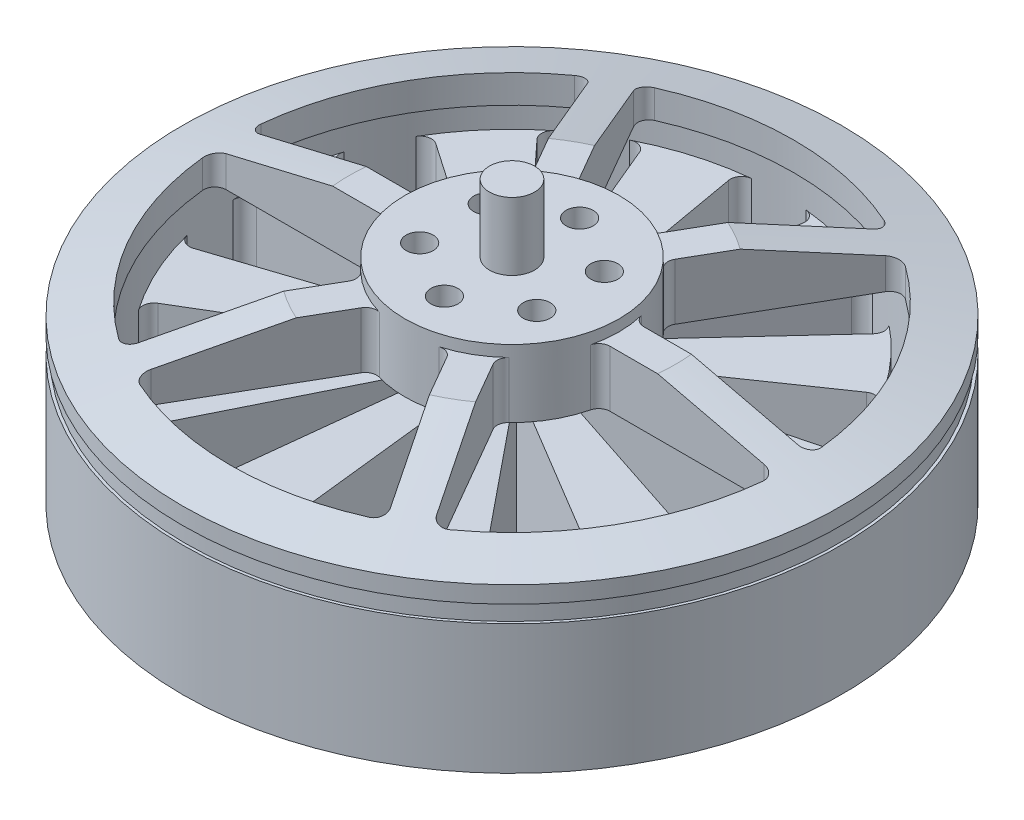
SolidWorks part; units mm, degrees
material "AISI 304"
ref_plane "前视基准面" through (0, 0, 0) normal (0, 0, 1) x (1, 0, 0)
ref_plane "上视基准面" through (0, 0, 0) normal (0, 1, 0) x (1, 0, 0)
ref_plane "右视基准面" through (0, 0, 0) normal (1, 0, 0) x (0, 0, -1)
sketch "Sketch1" plane through (0, 0, 0) normal (0, 1, 0) x (1, 0, 0)
  line L0 (0, 17.0731) -> (0, -17.4664) construction
  line L1 (-18.3889, 0) -> (24.4664, 0) construction
  line L2 (14.5, -3) -> (12.1347, -3)
  line L3 (2, 15.5) -> (-2, 15.5)
  line L4 (-3, 14.5) -> (-3, 12.1347)
  line L5 (3, 14.5) -> (3, 12.1347)
  line L6 (14.5, 3) -> (12.1347, 3)
  line L7 (15.5, -2) -> (15.5, 2)
  line L8 (-3, -14.5) -> (-3, -12.1347)
  line L9 (3, -14.5) -> (3, -12.1347)
  line L10 (-2, -15.5) -> (2, -15.5)
  line L11 (-14.5, 3) -> (-12.1347, 3)
  line L12 (-14.5, -3) -> (-12.1347, -3)
  line L13 (-15.5, 2) -> (-15.5, -2)
  arc A0 (-3, 12.1347) -> (-12.1347, 3) centre (0, 0) ccw
  circle A1 centre (0, 0) radius 6
  circle A2 centre (0, 12.5) radius 1.2
  arc A3 (3, 14.5) -> (2, 15.5) centre (2, 14.5) ccw
  arc A4 (-2, 15.5) -> (-3, 14.5) centre (-2, 14.5) ccw
  circle A5 centre (12.5, 0) radius 1.2
  arc A6 (15.5, 2) -> (14.5, 3) centre (14.5, 2) ccw
  arc A7 (14.5, -3) -> (15.5, -2) centre (14.5, -2) ccw
  circle A8 centre (0, -12.5) radius 1.2
  arc A9 (2, -15.5) -> (3, -14.5) centre (2, -14.5) ccw
  arc A10 (-3, -14.5) -> (-2, -15.5) centre (-2, -14.5) ccw
  circle A11 centre (-12.5, 0) radius 1.2
  arc A12 (-15.5, -2) -> (-14.5, -3) centre (-14.5, -2) ccw
  arc A13 (-14.5, 3) -> (-15.5, 2) centre (-14.5, 2) ccw
  arc A14 (-12.1347, -3) -> (-3, -12.1347) centre (0, 0) ccw
  arc A15 (12.1347, 3) -> (3, 12.1347) centre (0, 0) ccw
  arc A16 (3, -12.1347) -> (12.1347, -3) centre (0, 0) ccw
  circle A17 centre (0, 0) radius 8.5 construction
  arc A18 (-3, 7.953) -> (-7.953, 3) centre (0, 0) ccw construction
  arc A19 (-3.5647, 9.45) -> (-9.45, 3.5647) centre (0, 0) ccw
  arc A20 (-2.4353, 6.456) -> (-6.456, 2.4353) centre (0, 0) ccw
  arc A21 (-2.4353, 6.456) -> (-3.5647, 9.45) centre (-3, 7.953) ccw
  arc A22 (-9.45, 3.5647) -> (-6.456, 2.4353) centre (-7.953, 3) ccw
  arc A23 (7.953, 3) -> (3, 7.953) centre (0, 0) ccw construction
  arc A24 (9.45, 3.5647) -> (3.5647, 9.45) centre (0, 0) ccw
  arc A25 (6.456, 2.4353) -> (2.4353, 6.456) centre (0, 0) ccw
  arc A26 (6.456, 2.4353) -> (9.45, 3.5647) centre (7.953, 3) ccw
  arc A27 (3.5647, 9.45) -> (2.4353, 6.456) centre (3, 7.953) ccw
  arc A28 (3, -7.953) -> (7.953, -3) centre (0, 0) ccw construction
  arc A29 (3.5647, -9.45) -> (9.45, -3.5647) centre (0, 0) ccw
  arc A30 (2.4353, -6.456) -> (6.456, -2.4353) centre (0, 0) ccw
  arc A31 (2.4353, -6.456) -> (3.5647, -9.45) centre (3, -7.953) ccw
  arc A32 (9.45, -3.5647) -> (6.456, -2.4353) centre (7.953, -3) ccw
  arc A33 (-7.953, -3) -> (-3, -7.953) centre (0, 0) ccw construction
  arc A34 (-9.45, -3.5647) -> (-3.5647, -9.45) centre (0, 0) ccw
  arc A35 (-6.456, -2.4353) -> (-2.4353, -6.456) centre (0, 0) ccw
  arc A36 (-6.456, -2.4353) -> (-9.45, -3.5647) centre (-7.953, -3) ccw
  arc A37 (-3.5647, -9.45) -> (-2.4353, -6.456) centre (-3, -7.953) ccw
  point P16 (3, 15.5)
  point P19 (-3, 15.5)
  point P52 (0, 0)
  point P53 (-6.0104, 6.0104)
  point P63 (6.0104, 6.0104)
  point P70 (6.0104, -6.0104)
  point P77 (-6.0104, -6.0104)
  point P82 (0, 0)
  dimension "D1" = 25
  dimension "D2" = 12
  dimension "D5" = 2.4
  dimension "D6" = 1
  dimension "D9" = 17
  dimension "D12" = 1.6
  dimension "D3" = 15.5
  dimension "D4" = 6
  dimension "D7" = 12.5
  dimension "D10" = 3
  dimension "D11" = 3
  dimension "D8" = 4
  dimension "D13" = 4
extrude "Boss-Extrude1" add sketch "Sketch1" along normal blind 4.4
cosmetic thread "Cosmetic Thread1" parameters "D2"=3
cosmetic thread "Cosmetic Thread2" parameters "D2"=3
cosmetic thread "Cosmetic Thread3" parameters "D2"=3
cosmetic thread "Cosmetic Thread4" parameters "D2"=3
sketch "Sketch2" plane through (0, 4.4, 0) normal (0, 1, 0) x (1, 0, 0)
  arc A0 (-12.1347, -3) -> (-3, -12.1347) centre (0, 0) ccw
  arc A1 (-12.1347, -3) -> (-10.7247, -2.4457) centre (-12.5, 0) ccw
  arc A2 (-3, 12.1347) -> (-2.4457, 10.7247) centre (0, 12.5) ccw
  arc A3 (12.1347, 3) -> (10.7247, 2.4457) centre (12.5, 0) ccw
  arc A4 (3, -12.1347) -> (2.4457, -10.7247) centre (0, -12.5) ccw
  arc A5 (-3, 12.1347) -> (-12.1347, 3) centre (0, 0) ccw
  arc A6 (12.1347, 3) -> (3, 12.1347) centre (0, 0) ccw
  arc A7 (3, -12.1347) -> (12.1347, -3) centre (0, 0) ccw
  arc A8 (-10.7247, -2.4457) -> (-2.4457, -10.7247) centre (0, 0) ccw
  arc A9 (-2.4457, 10.7247) -> (-10.7247, 2.4457) centre (0, 0) ccw
  arc A10 (10.7247, 2.4457) -> (2.4457, 10.7247) centre (0, 0) ccw
  arc A11 (2.4457, -10.7247) -> (10.7247, -2.4457) centre (0, 0) ccw
  arc A12 (2.4457, 10.7247) -> (3, 12.1347) centre (0, 12.5) ccw
  arc A13 (10.7247, -2.4457) -> (12.1347, -3) centre (12.5, 0) ccw
  arc A14 (-2.4457, -10.7247) -> (-3, -12.1347) centre (0, -12.5) ccw
  arc A15 (-10.7247, 2.4457) -> (-12.1347, 3) centre (-12.5, 0) ccw
  point P18 (0, 0)
  point P24 (0, 0)
  point P25 (0, 0)
  point P26 (0, 0)
  dimension "D2" = 22
  dimension "D3" = 25
  dimension "D1" = 4
extrude "Boss-Extrude2" add sketch "Sketch2" along normal blind 4.4
sketch "Sketch3" plane through (0, 8.8, 0) normal (0, 1, 0) x (1, 0, 0)
  line L0 (-18.6186, 0) -> (21.8055, 0) construction
  line L1 (0, 15.9767) -> (0, -16.424) construction
  line L2 (-12.4789, 12.4789) -> (0, 0) construction
  line L3 (-8.4531, 7.0389) -> (-2.7071, 1.2929)
  line L4 (-7.0389, 8.4531) -> (-1.2929, 2.7071)
  line L5 (8.4531, 7.0389) -> (2.7071, 1.2929)
  line L6 (-13.186, 11.7718) -> (-0.7071, -0.7071) construction
  line L7 (-11.7718, 13.186) -> (0.7071, 0.7071) construction
  line L8 (7.0389, 8.4531) -> (1.2929, 2.7071)
  line L9 (7.0389, -8.4531) -> (1.2929, -2.7071)
  line L10 (8.4531, -7.0389) -> (2.7071, -1.2929)
  line L11 (-8.4531, -7.0389) -> (-2.7071, -1.2929)
  line L12 (-7.0389, -8.4531) -> (-1.2929, -2.7071)
  arc A0 (-2.7071, 1.2929) -> (-2.7071, -1.2929) centre (0, 0) ccw
  arc A1 (-7.0389, 8.4531) -> (-8.4531, 7.0389) centre (0, 0) ccw
  arc A2 (8.4531, 7.0389) -> (7.0389, 8.4531) centre (0, 0) ccw
  arc A3 (7.0389, -8.4531) -> (8.4531, -7.0389) centre (0, 0) ccw
  arc A4 (-8.4531, -7.0389) -> (-7.0389, -8.4531) centre (0, 0) ccw
  arc A5 (1.2929, 2.7071) -> (-1.2929, 2.7071) centre (0, 0) ccw
  arc A6 (2.7071, -1.2929) -> (2.7071, 1.2929) centre (0, 0) ccw
  arc A7 (-1.2929, -2.7071) -> (1.2929, -2.7071) centre (0, 0) ccw
  point P30 (0, 0)
  dimension "D1" = 6
  dimension "D5" = 22
  dimension "D2" = 45
  dimension "D3" = 1
  dimension "D4" = 1
  dimension "D6" = 4
extrude "Boss-Extrude3" add sketch "Sketch3" against normal blind 4.4
sketch "Sketch4" plane through (0, 4.4, 0) normal (0, -1, 0) x (1, 0, 0)
  circle A0 centre (0, 0) radius 3
extrude "Boss-Extrude4" add sketch "Sketch4" along normal blind 6
sketch "Sketch5" plane through (0, 8.8, 0) normal (0, 1, 0) x (1, 0, 0)
  circle A0 centre (0, 0) radius 2
  dimension "D1" = 4
extrude "Boss-Extrude5" add sketch "Sketch5" along normal blind 25
sketch "Sketch6" plane through (0, 0, 0) normal (0, 0, 1) x (1, 0, 0)
  line L0 (0, 28.4377) -> (0, -3.1922) construction
  line L1 (-25.25, 8.8) -> (-29.25, 8.8)
  line L3 (-29.25, 8.8) -> (-29.25, 23.3)
  line L4 (-29.25, 23.3) -> (-14.5, 26.8)
  line L5 (-14.5, 26.8) -> (-9.5, 26.8)
  line L6 (-9.5, 26.8) -> (-9.5, 27.8)
  line L7 (-9.5, 27.8) -> (0, 27.8)
  line L8 (-12.1347, 0) -> (-3, 0) construction
  line L10 (0, 27.8) -> (0, 21.8)
  line L11 (0, 21.8) -> (-25.25, 21.8)
  line L12 (-25.25, 21.8) -> (-25.25, 8.8)
  dimension "D1" = 27.8
  dimension "D2" = 9.5
  dimension "D3" = 5
  dimension "D4" = 29.25
  dimension "D5" = 1
  dimension "D6" = 14.5
  dimension "D7" = 4
  dimension "D8" = 6
revolve "Revolve2" add sketch "Sketch6" angle 360 about L0
sketch "Sketch7" plane through (0, 26.8, 0) normal (0, 1, 0) x (1, 0, 0)
  line L0 (-38.4586, 0) -> (33.9217, 0) construction
  line L1 (0, 30.0441) -> (0, -31.152) construction
  line L2 (-10.6357, 21.4215) -> (-3.8, 9.5818)
  line L3 (0, 0) -> (-16.9032, 29.2772) construction
  line L4 (0, 0) -> (16.9032, 29.2772) construction
  line L5 (10.6357, 21.4215) -> (3.8, 9.5818)
  line L6 (13.2338, 19.9215) -> (6.3981, 8.0818)
  line L7 (23.8694, 1.5) -> (10.198, 1.5)
  line L8 (23.8694, -1.5) -> (10.198, -1.5)
  line L9 (13.2338, -19.9215) -> (6.3981, -8.0818)
  line L10 (10.6357, -21.4215) -> (3.8, -9.5818)
  line L11 (-10.6357, -21.4215) -> (-3.8, -9.5818)
  line L12 (-13.2338, -19.9215) -> (-6.3981, -8.0818)
  line L13 (-23.8694, -1.5) -> (-10.198, -1.5)
  line L14 (-23.8694, 1.5) -> (-10.198, 1.5)
  line L15 (-13.2338, 19.9215) -> (-6.3981, 8.0818)
  arc A2 (10.1767, 22.8349) -> (-10.1767, 22.8349) centre (0, 0) ccw
  arc A3 (2.6545, 9.1216) -> (-2.6545, 9.1216) centre (0, 0) ccw
  arc A4 (-3.8, 9.5818) -> (-2.6545, 9.1216) centre (-2.934, 10.0818) ccw
  arc A5 (3.8, 9.5818) -> (2.6545, 9.1216) centre (2.934, 10.0818) cw
  arc A6 (10.6357, 21.4215) -> (10.1767, 22.8349) centre (9.7697, 21.9215) ccw
  arc A7 (-10.6357, 21.4215) -> (-10.1767, 22.8349) centre (-9.7697, 21.9215) cw
  arc A8 (13.2338, 19.9215) -> (14.6873, 20.2308) centre (14.0998, 19.4215) cw
  arc A9 (6.3981, 8.0818) -> (6.5723, 6.8597) centre (7.2641, 7.5818) ccw
  arc A10 (9.2268, 2.2619) -> (6.5723, 6.8597) centre (0, 0) ccw
  arc A11 (10.198, 1.5) -> (9.2268, 2.2619) centre (10.198, 2.5) cw
  arc A12 (23.8694, 1.5) -> (24.864, 2.6042) centre (23.8694, 2.5) ccw
  arc A13 (24.864, 2.6042) -> (14.6873, 20.2308) centre (0, 0) ccw
  arc A14 (23.8694, -1.5) -> (24.864, -2.6042) centre (23.8694, -2.5) cw
  arc A15 (10.198, -1.5) -> (9.2268, -2.2619) centre (10.198, -2.5) ccw
  arc A16 (6.5723, -6.8597) -> (9.2268, -2.2619) centre (0, 0) ccw
  arc A17 (6.3981, -8.0818) -> (6.5723, -6.8597) centre (7.2641, -7.5818) cw
  arc A18 (13.2338, -19.9215) -> (14.6873, -20.2308) centre (14.0998, -19.4215) ccw
  arc A19 (14.6873, -20.2308) -> (24.864, -2.6042) centre (0, 0) ccw
  arc A20 (10.6357, -21.4215) -> (10.1767, -22.8349) centre (9.7697, -21.9215) cw
  arc A21 (3.8, -9.5818) -> (2.6545, -9.1216) centre (2.934, -10.0818) ccw
  arc A22 (-2.6545, -9.1216) -> (2.6545, -9.1216) centre (0, 0) ccw
  arc A23 (-3.8, -9.5818) -> (-2.6545, -9.1216) centre (-2.934, -10.0818) cw
  arc A24 (-10.6357, -21.4215) -> (-10.1767, -22.8349) centre (-9.7697, -21.9215) ccw
  arc A25 (-10.1767, -22.8349) -> (10.1767, -22.8349) centre (0, 0) ccw
  arc A26 (-13.2338, -19.9215) -> (-14.6873, -20.2308) centre (-14.0998, -19.4215) cw
  arc A27 (-6.3981, -8.0818) -> (-6.5723, -6.8597) centre (-7.2641, -7.5818) ccw
  arc A28 (-9.2268, -2.2619) -> (-6.5723, -6.8597) centre (0, 0) ccw
  arc A29 (-10.198, -1.5) -> (-9.2268, -2.2619) centre (-10.198, -2.5) cw
  arc A30 (-23.8694, -1.5) -> (-24.864, -2.6042) centre (-23.8694, -2.5) ccw
  arc A31 (-24.864, -2.6042) -> (-14.6873, -20.2308) centre (0, 0) ccw
  arc A32 (-23.8694, 1.5) -> (-24.864, 2.6042) centre (-23.8694, 2.5) cw
  arc A33 (-10.198, 1.5) -> (-9.2268, 2.2619) centre (-10.198, 2.5) ccw
  arc A34 (-6.5723, 6.8597) -> (-9.2268, 2.2619) centre (0, 0) ccw
  arc A35 (-6.3981, 8.0818) -> (-6.5723, 6.8597) centre (-7.2641, 7.5818) cw
  arc A36 (-13.2338, 19.9215) -> (-14.6873, 20.2308) centre (-14.0998, 19.4215) ccw
  arc A37 (-14.6873, 20.2308) -> (-24.864, 2.6042) centre (0, 0) ccw
  point P12 (-3.3914, 8.874)
  point P17 (3.3914, 8.874)
  point P85 (0, 0)
  dimension "D1" = 25
  dimension "D2" = 9.5
  dimension "D7" = 1
  dimension "D3" = 1.5
  dimension "D4" = 30
  dimension "D5" = 30
  dimension "D6" = 6.7828
  dimension "D8" = 6
extrude "Cut-Extrude1" cut sketch "Sketch7" against normal blind 19
sketch "Sketch8" plane through (0, 0, 0) normal (0, 0, 1) x (1, 0, 0)
  line L0 (0, 34.8317) -> (0, -3.8139) construction
  line L1 (0, 20.8) -> (-23.8, 20.8)
  line L2 (-23.8, 20.8) -> (-23.8, 8.8)
  line L3 (-25.25, 8.8) -> (25.25, 8.8) construction
  line L4 (-23.8, 8.8) -> (0, 8.8)
  line L5 (0, 20.8) -> (0, 8.8)
  dimension "D1" = 12
  dimension "D2" = 23.8
revolve "Revolve3" add sketch "Sketch8" angle 360 about L0
sketch "Sketch9" plane through (0, 20.8, 0) normal (0, 1, 0) x (1, 0, 0)
  line L0 (0, 24.4521) -> (0, 3.8491) construction
  line L1 (-3.2903, 22.5095) -> (0, 3.8491)
  line L2 (3.2903, 22.5095) -> (0, 3.8491)
  line L3 (9.4015, 20.7151) -> (2.081, 3.2381)
  line L4 (14.9375, 17.1573) -> (2.081, 3.2381)
  line L5 (19.1085, 12.3438) -> (3.5013, 1.599)
  line L6 (21.8422, 6.3578) -> (3.5013, 1.599)
  line L7 (22.7486, 0.0534) -> (3.8099, -0.5478)
  line L8 (21.8121, -6.4603) -> (3.8099, -0.5478)
  line L9 (19.1662, -12.2539) -> (2.9089, -2.5206)
  line L10 (14.8568, -17.2272) -> (2.9089, -2.5206)
  line L11 (9.4987, -20.6707) -> (1.0844, -3.6932)
  line L12 (3.1846, -22.5247) -> (1.0844, -3.6932)
  line L13 (-3.1846, -22.5247) -> (-1.0844, -3.6932)
  line L14 (-9.4987, -20.6707) -> (-1.0844, -3.6932)
  line L15 (-14.8568, -17.2272) -> (-2.9089, -2.5206)
  line L16 (-19.1662, -12.2539) -> (-2.9089, -2.5206)
  line L17 (-21.8121, -6.4603) -> (-3.8099, -0.5478)
  line L18 (-22.7486, 0.0534) -> (-3.8099, -0.5478)
  line L19 (-21.8422, 6.3578) -> (-3.5013, 1.599)
  line L20 (-19.1085, 12.3438) -> (-3.5013, 1.599)
  line L21 (-14.9375, 17.1573) -> (-2.081, 3.2381)
  line L22 (-9.4015, 20.7151) -> (-2.081, 3.2381)
  circle A0 centre (0, 0) radius 23.8 construction
  arc A1 (2.4066, 23.678) -> (-2.4066, 23.678) centre (0, 0) ccw
  arc A2 (3.2903, 22.5095) -> (2.4066, 23.678) centre (2.3055, 22.6831) ccw
  arc A3 (-3.2903, 22.5095) -> (-2.4066, 23.678) centre (-2.3055, 22.6831) cw
  arc A4 (14.8259, 18.6181) -> (10.7767, 21.2203) centre (0, 0) ccw
  arc A5 (9.4015, 20.7151) -> (10.7767, 21.2203) centre (10.3239, 20.3287) cw
  arc A6 (14.9375, 17.1573) -> (14.8259, 18.6181) centre (14.203, 17.8358) ccw
  arc A7 (22.538, 7.647) -> (20.5385, 12.0254) centre (0, 0) ccw
  arc A8 (19.1085, 12.3438) -> (20.5385, 12.0254) centre (19.6756, 11.5201) cw
  arc A9 (21.8422, 6.3578) -> (22.538, 7.647) centre (21.5911, 7.3257) ccw
  arc A10 (23.0945, -5.7519) -> (23.7795, -0.9876) centre (0, 0) ccw
  arc A11 (22.7486, 0.0534) -> (23.7795, -0.9876) centre (22.7804, -0.9461) cw
  arc A12 (21.8121, -6.4603) -> (23.0945, -5.7519) centre (22.1241, -5.5102) ccw
  arc A13 (16.3186, -17.3246) -> (19.4707, -13.687) centre (0, 0) ccw
  arc A14 (19.1662, -12.2539) -> (19.4707, -13.687) centre (18.6526, -13.1119) cw
  arc A15 (14.8568, -17.2272) -> (16.3186, -17.3246) centre (15.633, -16.5967) ccw
  arc A16 (4.3617, -23.3969) -> (8.98, -22.0409) centre (0, 0) ccw
  arc A17 (9.4987, -20.6707) -> (8.98, -22.0409) centre (8.6027, -21.1148) cw
  arc A18 (3.1846, -22.5247) -> (4.3617, -23.3969) centre (4.1784, -22.4138) ccw
  arc A19 (-8.98, -22.0409) -> (-4.3617, -23.3969) centre (0, 0) ccw
  arc A20 (-3.1846, -22.5247) -> (-4.3617, -23.3969) centre (-4.1784, -22.4138) cw
  arc A21 (-9.4987, -20.6707) -> (-8.98, -22.0409) centre (-8.6027, -21.1148) ccw
  arc A22 (-19.4707, -13.687) -> (-16.3186, -17.3246) centre (0, 0) ccw
  arc A23 (-14.8568, -17.2272) -> (-16.3186, -17.3246) centre (-15.633, -16.5967) cw
  arc A24 (-19.1662, -12.2539) -> (-19.4707, -13.687) centre (-18.6526, -13.1119) ccw
  arc A25 (-23.7795, -0.9876) -> (-23.0945, -5.7519) centre (0, 0) ccw
  arc A26 (-21.8121, -6.4603) -> (-23.0945, -5.7519) centre (-22.1241, -5.5102) cw
  arc A27 (-22.7486, 0.0534) -> (-23.7795, -0.9876) centre (-22.7804, -0.9461) ccw
  arc A28 (-20.5385, 12.0254) -> (-22.538, 7.647) centre (0, 0) ccw
  arc A29 (-21.8422, 6.3578) -> (-22.538, 7.647) centre (-21.5911, 7.3257) cw
  arc A30 (-19.1085, 12.3438) -> (-20.5385, 12.0254) centre (-19.6756, 11.5201) ccw
  arc A31 (-10.7767, 21.2203) -> (-14.8259, 18.6181) centre (0, 0) ccw
  arc A32 (-14.9375, 17.1573) -> (-14.8259, 18.6181) centre (-14.203, 17.8358) cw
  arc A33 (-9.4015, 20.7151) -> (-10.7767, 21.2203) centre (-10.3239, 20.3287) ccw
  point P12 (3.473, 23.5452)
  point P15 (-3.473, 23.5452)
  point P87 (0, 0)
  dimension "D3" = 1
  dimension "D1" = 10
  dimension "D2" = 20
  dimension "D4" = 11
extrude "Cut-Extrude2" cut sketch "Sketch9" against normal blind 12 contours A1 A3 L1 L2 A2 | L3 L4 A6 A4 A5 | L5 L6 A9 A7 A8 | L7 L8 A12 A10 A11 | L9 L10 A15 A13 A14 | L11 L12 A18 A16 A17 | L13 L14 A21 A19 A20 | L15 L16 A24 A22 A23 | L17 L18 A27 A25 A26 | L19 L20 A30 A28 A29 | L21 L22 A33 A31 A32
sketch "Sketch10" plane through (0, 27.8, 0) normal (0, 1, 0) x (1, 0, 0)
  circle A0 centre (0, 0) radius 6 construction
  circle A1 centre (0, 6) radius 1.2
  circle A2 centre (5.1962, 3) radius 1.2
  circle A3 centre (5.1962, -3) radius 1.2
  circle A4 centre (0, -6) radius 1.2
  circle A5 centre (-5.1962, -3) radius 1.2
  circle A6 centre (-5.1962, 3) radius 1.2
  point P17 (0, 0)
  dimension "D1" = 12
  dimension "D2" = 2.4
  dimension "D4" = 12
  dimension "D3" = 6
extrude "Cut-Extrude3" cut sketch "Sketch10" against normal blind 6
cosmetic thread "Cosmetic Thread5" parameters "D2"=3
cosmetic thread "Cosmetic Thread6" parameters "D2"=3
cosmetic thread "Cosmetic Thread7" parameters "D2"=3
cosmetic thread "Cosmetic Thread8" parameters "D2"=3
cosmetic thread "Cosmetic Thread9" parameters "D2"=3
cosmetic thread "Cosmetic Thread10" parameters "D2"=3
sketch "Sketch11" plane through (0, 0, 0) normal (0, 0, 1) x (1, 0, 0)
  line L0 (0, 34.7094) -> (0, -4.9961) construction
  line L1 (-31, 21.8) -> (-29, 21.8)
  line L2 (-29, 21.8) -> (-29, 20.3)
  line L3 (-29, 20.3) -> (-31, 20.3)
  line L4 (-31, 20.3) -> (-31, 21.8)
  line L5 (2, 33.8) -> (-2, 33.8) construction
  dimension "D1" = 29
  dimension "D2" = 2
  dimension "D3" = 1.5
  dimension "D4" = 12
revolve "Cut-Revolve1" cut sketch "Sketch11" angle 360 about L0
